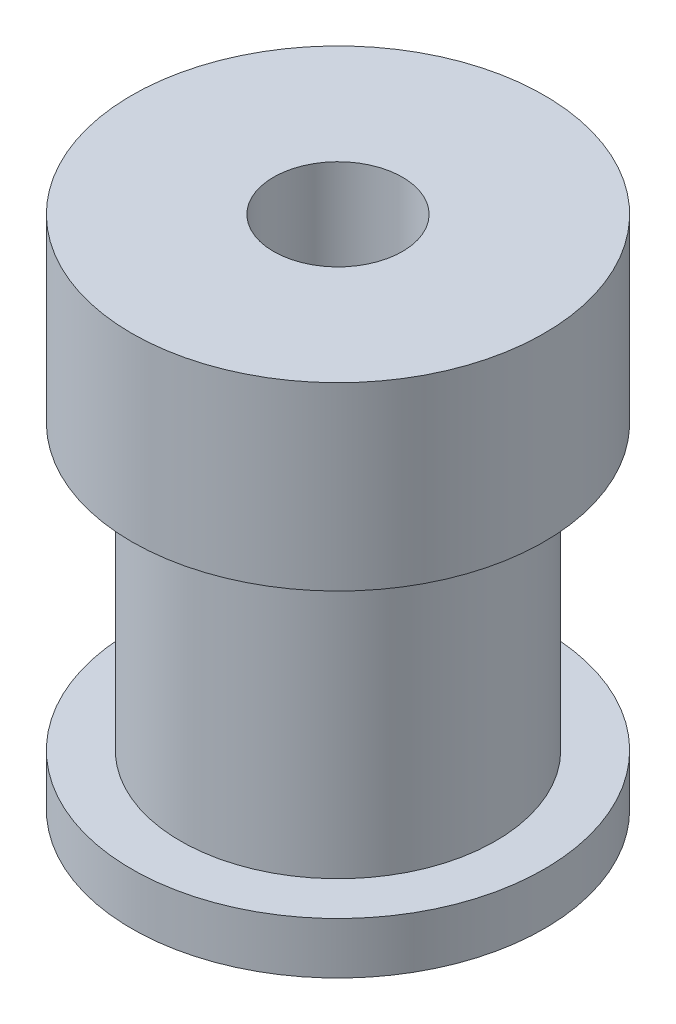
SolidWorks part; units mm, degrees
material "AISI 304"
ref_plane "前视基准面" through (0, 0, 0) normal (0, 0, 1) x (1, 0, 0)
ref_plane "上视基准面" through (0, 0, 0) normal (0, 1, 0) x (1, 0, 0)
ref_plane "右视基准面" through (0, 0, 0) normal (1, 0, 0) x (0, 0, -1)
other "Configuration Table"
sketch "草图1" plane through (0, 0, 0) normal (0, 1, 0) x (1, 0, 0)
  circle A0 centre (0, 0) radius 8
  dimension "D1" = 16
extrude "凸台-拉伸1" add sketch "草图1" along normal blind 7
sketch "草图2" plane through (0, 0, 0) normal (0, -1, 0) x (1, 0, 0)
  circle A0 centre (0, 0) radius 6.11
  dimension "D1" = 12.22
extrude "凸台-拉伸2" add sketch "草图2" along normal blind 11
sketch "草图3" plane through (0, -11, 0) normal (0, -1, 0) x (1, 0, 0)
  circle A0 centre (0, 0) radius 8
  dimension "D1" = 16
extrude "凸台-拉伸3" add sketch "草图3" along normal blind 2
sketch "草图4" plane through (0, 7, 0) normal (0, 1, 0) x (1, 0, 0)
  circle A0 centre (0, 0) radius 2.5
  dimension "D1" = 5
extrude "切除-拉伸1" cut sketch "草图4" against normal blind 25 contours A0
